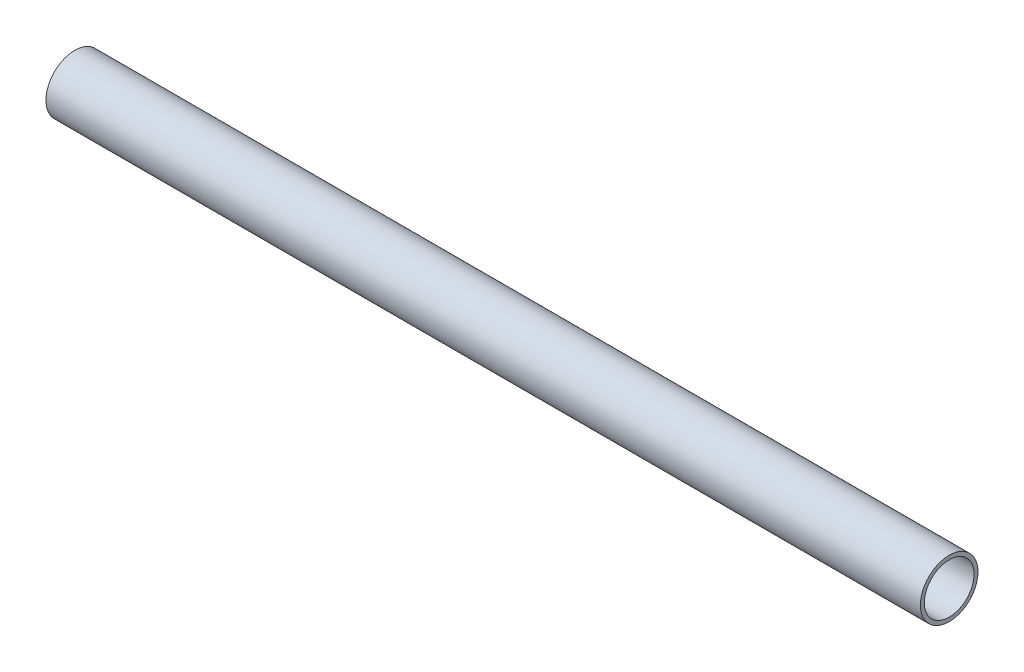
SolidWorks part; units mm, degrees
material "PVC 0.007 Plasticized"
ref_plane "Front Plane" through (0, 0, 0) normal (0, 0, 1) x (1, 0, 0)
ref_plane "Top Plane" through (0, 0, 0) normal (0, 1, 0) x (1, 0, 0)
ref_plane "Right Plane" through (0, 0, 0) normal (1, 0, 0) x (0, 0, -1)
sketch "Sketch1" plane through (0, 0, 0) normal (1, 0, 0) x (0, 0, -1)
  circle A0 centre (0, 0) radius 11
  circle A1 centre (0, 0) radius 9.5
  dimension "D1" = 1.5
extrude "Boss-Extrude1" add sketch "Sketch1" along normal blind 24 and the other way blind 310
